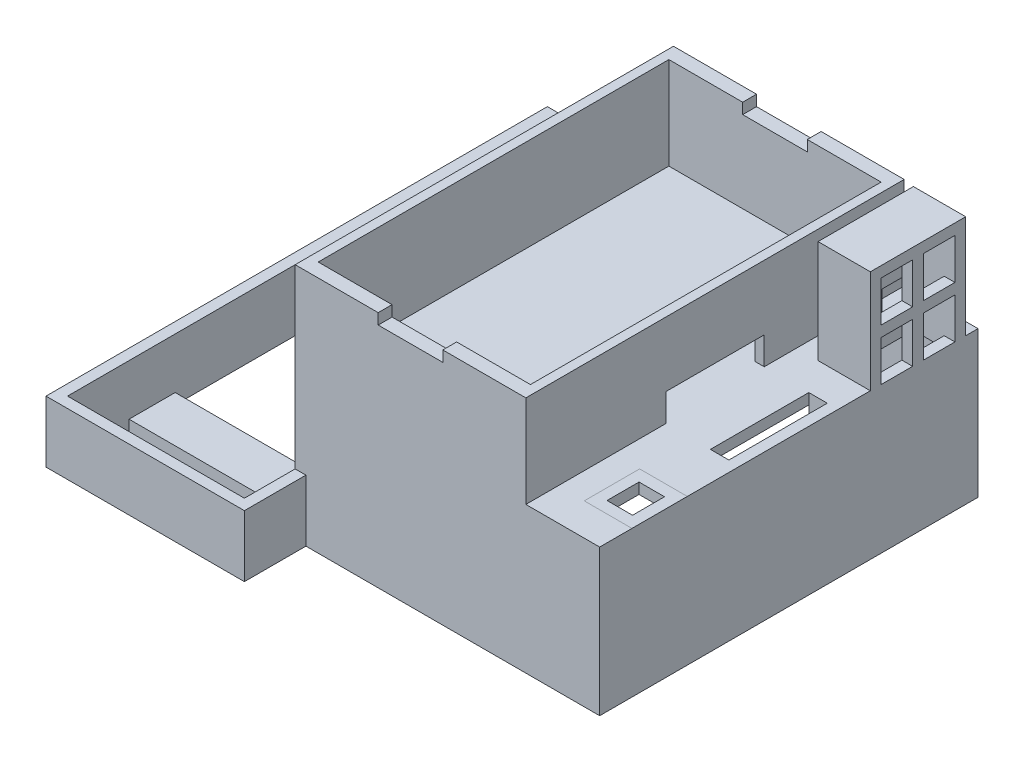
SolidWorks part; units mm, degrees
ref_plane "Front Plane" through (0, 0, 0) normal (0, 0, 1) x (1, 0, 0)
ref_plane "Top Plane" through (0, 0, 0) normal (0, 1, 0) x (1, 0, 0)
ref_plane "Right Plane" through (0, 0, 0) normal (1, 0, 0) x (0, 0, -1)
sketch "Sketch1" plane through (0, 0, 0) normal (0, 1, 0) x (1, 0, 0)
  line L1 (-138.162, -76.1412) -> (-88.662, -76.1412)
  line L2 (-138.162, -76.1412) -> (-138.162, -14.6412)
  line L3 (-138.162, -14.6412) -> (-88.662, -14.6412)
  line L4 (-88.662, -76.1412) -> (-88.662, -14.6412)
  dimension "D1" = 49.5
  dimension "D2" = 61.5
extrude "Boss-Extrude1" add sketch "Sketch1" along normal blind 23.75
sketch "Sketch2" plane through (0, 0, 0) normal (0, -1, 0) x (-1, 0, 0)
  line L0 (138.162, -76.1412) -> (88.662, -76.1412) construction
  line L1 (90.412, -74.3912) -> (136.412, -74.3912)
  line L2 (90.412, -74.3912) -> (90.412, -16.3912)
  line L3 (90.412, -16.3912) -> (136.412, -16.3912)
  line L4 (136.412, -74.3912) -> (136.412, -16.3912)
  line L5 (88.662, -76.1412) -> (88.662, -14.6412) construction
  line L6 (88.662, -14.6412) -> (138.162, -14.6412) construction
  line L7 (138.162, -14.6412) -> (138.162, -76.1412) construction
  dimension "D1" = 1.75
  dimension "D2" = 1.75
  dimension "D3" = 1.75
  dimension "D4" = 1.75
extrude "Cut-Extrude1" cut sketch "Sketch2" against normal blind 22
sketch "Sketch3" plane through (0, 22, 0) normal (0, -1, 0) x (-1, 0, 0)
  line L0 (136.412, -16.3912) -> (90.412, -16.3912) construction
  line L1 (90.412, -74.3912) -> (93.412, -74.3912)
  line L2 (90.412, -74.3912) -> (90.412, -16.3912)
  line L3 (90.412, -16.3912) -> (93.412, -16.3912)
  line L4 (93.412, -74.3912) -> (93.412, -16.3912)
  line L6 (90.412, -58.3912) -> (93.412, -58.3912)
  line L7 (90.412, -58.3912) -> (90.412, -53.3912)
  line L8 (90.412, -53.3912) -> (93.412, -53.3912)
  line L9 (93.412, -58.3912) -> (93.412, -53.3912)
  line L10 (90.412, -37.3912) -> (93.412, -37.3912)
  line L11 (90.412, -37.3912) -> (90.412, -32.3912)
  line L12 (90.412, -32.3912) -> (93.412, -32.3912)
  line L13 (93.412, -37.3912) -> (93.412, -32.3912)
  line M9 (90.412, -16.3912) -> (90.412, -74.3912)
  line M10 (90.412, -74.3912) -> (136.412, -74.3912)
  line M12 (136.412, -16.3912) -> (90.412, -16.3912)
  dimension "D1" = 3
  dimension "D2" = 5
  dimension "D3" = 5
  dimension "D4" = 16
  dimension "D5" = 16
extrude "Cut-Extrude2" cut sketch "Sketch3" against normal blind 1.75 contours L6 L2 L4 M10 | L12 L4 M9 M12 | L10 L2 L8 L4
sketch "Sketch7" plane through (0, 22, 0) normal (0, -1, 0) x (-1, 0, 0)
  line L1 (90.412, -58.3912) -> (93.412, -58.3912)
  line L2 (90.412, -58.3912) -> (90.412, -53.3912)
  line L3 (90.412, -53.3912) -> (93.412, -53.3912)
  line L4 (93.412, -58.3912) -> (93.412, -53.3912)
  line L5 (90.412, -37.3912) -> (93.412, -37.3912)
  line L6 (90.412, -37.3912) -> (90.412, -32.3912)
  line L7 (90.412, -32.3912) -> (93.412, -32.3912)
  line L8 (93.412, -37.3912) -> (93.412, -32.3912)
extrude "Boss-Extrude2" add sketch "Sketch7" along normal blind 6 contours L2 L1 L4 L3 | L6 L5 L8 L7
sketch "Sketch9" plane through (-93.412, 0, 0) normal (-1, 0, 0) x (0, 0, 1)
  line L0 (58.3912, 16) -> (58.3912, 22) construction
  line L1 (58.3912, 20.407) -> (53.3912, 20.407)
  line L2 (58.3912, 20.407) -> (58.3912, 22)
  line L3 (58.3912, 22) -> (53.3912, 22)
  line L4 (53.3912, 20.407) -> (53.3912, 22)
sketch "Sketch11" plane through (0, 23.75, 0) normal (0, 1, 0) x (1, 0, 0)
  line L0 (-138.162, -76.1412) -> (-88.662, -76.1412) construction
  line L1 (-138.162, -14.6412) -> (-100.662, -14.6412)
  line L2 (-138.162, -14.6412) -> (-138.162, -76.1412)
  line L3 (-138.162, -76.1412) -> (-100.662, -76.1412)
  line L4 (-100.662, -14.6412) -> (-100.662, -76.1412)
  dimension "D1" = 37.5
extrude "Boss-Extrude3" add sketch "Sketch11" along normal blind 15
sketch "Sketch12" plane through (0, 38.75, 0) normal (0, 1, 0) x (1, 0, 0)
  line L0 (-138.162, -14.6412) -> (-138.162, -76.1412) construction
  line L1 (-136.662, -16.8912) -> (-102.162, -16.8912)
  line L2 (-136.662, -16.8912) -> (-136.662, -73.8912)
  line L3 (-136.662, -73.8912) -> (-102.162, -73.8912)
  line L4 (-102.162, -16.8912) -> (-102.162, -73.8912)
  line L5 (-100.662, -76.1412) -> (-100.662, -14.6412) construction
  line L6 (-100.662, -14.6412) -> (-138.162, -14.6412) construction
  line L7 (-138.162, -76.1412) -> (-100.662, -76.1412) construction
  dimension "D1" = 1.5
  dimension "D2" = 1.5
  dimension "D3" = 2.25
  dimension "D4" = 2.25
extrude "Cut-Extrude3" cut sketch "Sketch12" against normal blind 15
sketch "Sketch14" plane through (0, 23.75, 0) normal (0, 1, 0) x (1, 0, 0)
  line L0 (-90.412, -58.3912) -> (-93.412, -58.3912) construction
  line L1 (-96.417, -70.8912) -> (-88.667, -70.8912)
  line L2 (-96.417, -70.8912) -> (-96.417, -61.8912)
  line L3 (-96.417, -61.8912) -> (-88.667, -61.8912)
  line L4 (-88.667, -70.8912) -> (-88.667, -61.8912)
  point P6 (-91.912, -58.3912)
  dimension "D1" = 9
  dimension "D2" = 7.75
  dimension "D3" = 3.5
  dimension "D4" = 3.245
extrude "Boss-Extrude4" add sketch "Sketch14" along normal blind 0.0001
sketch "Sketch15" plane through (0, 23.7501, 0) normal (0, 1, 0) x (1, 0, 0)
  line L0 (-96.417, -61.8912) -> (-96.417, -70.8912) construction
  line L1 (-94.617, -68.9912) -> (-90.467, -68.9912)
  line L2 (-94.617, -68.9912) -> (-94.617, -63.7912)
  line L3 (-94.617, -63.7912) -> (-90.467, -63.7912)
  line L4 (-90.467, -68.9912) -> (-90.467, -63.7912)
  line L5 (-88.667, -61.8912) -> (-96.417, -61.8912) construction
  line L6 (-88.667, -70.8912) -> (-88.667, -61.8912) construction
  line L7 (-96.417, -70.8912) -> (-88.667, -70.8912) construction
  dimension "D1" = 1.8
  dimension "D2" = 1.9
  dimension "D3" = 1.8
  dimension "D4" = 1.9
extrude "Cut-Extrude4" cut sketch "Sketch15" against normal blind 4.75
sketch "Sketch16" plane through (0, 23.75, 0) normal (0, 1, 0) x (1, 0, 0)
  line L0 (-93.412, -16.3912) -> (-90.412, -16.3912) construction
  line L1 (-97.162, -32.1412) -> (-88.662, -32.1412)
  line L2 (-97.162, -32.1412) -> (-97.162, -16.6412)
  line L3 (-97.162, -16.6412) -> (-88.662, -16.6412)
  line L4 (-88.662, -32.1412) -> (-88.662, -16.6412)
  line L5 (-93.412, -32.3912) -> (-93.412, -16.3912) construction
  point P6 (-91.912, -16.3912)
  point P9 (-93.412, -24.3912)
  dimension "D1" = 15.5
  dimension "D2" = 8.5
  dimension "D3" = 3.25
  dimension "D4" = 7.75
extrude "Boss-Extrude5" add sketch "Sketch16" along normal blind 16.75
sketch "Sketch17" plane through (-88.662, 0, 0) normal (1, 0, 0) x (0, 0, -1)
  line L0 (-32.1412, 40.5) -> (-16.6412, 40.5) construction
  line L1 (-30.3912, 38.75) -> (-25.2662, 38.75)
  line L2 (-30.3912, 38.75) -> (-30.3912, 23.75)
  line L3 (-30.3912, 23.75) -> (-25.2662, 23.75)
  line L4 (-25.2662, 38.75) -> (-25.2662, 23.75)
  line L5 (-23.5162, 38.75) -> (-18.3912, 38.75)
  line L6 (-23.5162, 38.75) -> (-23.5162, 23.75)
  line L7 (-23.5162, 23.75) -> (-18.3912, 23.75)
  line L8 (-18.3912, 38.75) -> (-18.3912, 23.75)
  line L9 (-32.1412, 40.5) -> (-32.1412, 23.75) construction
  line L10 (-16.6412, 40.5) -> (-16.6412, 23.75) construction
  line L11 (-16.6412, 23.75) -> (-14.6412, 23.75) construction
  line L12 (-76.1412, 23.75) -> (-32.1412, 23.75) construction
  line L14 (-32.1412, 32.125) -> (-16.6412, 32.125)
  line L15 (-32.1412, 32.125) -> (-32.1412, 30.375)
  line L16 (-32.1412, 30.375) -> (-16.6412, 30.375)
  line L17 (-16.6412, 32.125) -> (-16.6412, 30.375)
  dimension "D1" = 1.75
  dimension "D2" = 1.75
  dimension "D3" = 1.75
  dimension "D4" = 1.75
  dimension "D5" = 0
  dimension "D6" = 0
  dimension "D7" = 5.125
  dimension "D8" = 5.125
  dimension "D9" = 1.75
  dimension "D10" = 6.625
extrude "Cut-Extrude5" cut sketch "Sketch17" against normal blind 8.5 contours L2 L14 L4 L1 | L16 L2 L3 L4 | L6 L14 L8 L5 | L16 L6 L7 L8
sketch "Sketch18" plane through (0, 23.75, 0) normal (0, 1, 0) x (1, 0, 0)
  line L0 (-93.412, -18.3912) -> (-90.412, -18.3912) construction
  line L1 (-95.412, -30.3912) -> (-90.412, -30.3912)
  line L2 (-95.412, -30.3912) -> (-95.412, -18.3912)
  line L3 (-95.412, -18.3912) -> (-90.412, -18.3912)
  line L4 (-90.412, -30.3912) -> (-90.412, -18.3912)
  line L5 (-88.662, -30.3912) -> (-88.662, -25.2662) construction
  line L6 (-93.412, -30.3912) -> (-90.412, -30.3912) construction
  dimension "D1" = 0
  dimension "D2" = 1.75
  dimension "D3" = 1.75
  dimension "D4" = 0
extrude "Cut-Extrude6" cut sketch "Sketch18" against normal blind 1.75 and the other way blind 15
sketch "Sketch20" plane through (-100.662, 0, 0) normal (1, 0, 0) x (0, 0, -1)
  line L0 (-76.1412, 23.75) -> (-14.6412, 23.75) construction
  line L1 (-53.3912, 28.25) -> (-37.3912, 28.25)
  line L2 (-53.3912, 28.25) -> (-53.3912, 23.75)
  line L3 (-53.3912, 23.75) -> (-37.3912, 23.75)
  line L4 (-37.3912, 28.25) -> (-37.3912, 23.75)
  dimension "D1" = 4.5
  dimension "D2" = 0
  dimension "D3" = 0
extrude "Cut-Extrude7" cut sketch "Sketch20" against normal blind 1.75
sketch "Sketch21" plane through (0, 0, 0) normal (0, -1, 0) x (-1, 0, 0)
  line L0 (138.162, -14.6412) -> (138.162, -76.1412) construction
  line L1 (136.412, -86.1412) -> (168.662, -86.1412)
  line L2 (136.412, -86.1412) -> (136.412, -4.6412)
  line L3 (136.412, -4.6412) -> (168.662, -4.6412)
  line L4 (168.662, -86.1412) -> (168.662, -4.6412)
  line L5 (138.162, -76.1412) -> (88.662, -76.1412) construction
  line L6 (88.662, -14.6412) -> (138.162, -14.6412) construction
  dimension "D1" = 30.5
  dimension "D2" = 1.75
  dimension "D3" = 10
  dimension "D4" = 10
extrude "Boss-Extrude7" add sketch "Sketch21" against normal blind 10
sketch "Sketch23" plane through (0, 10, 0) normal (0, 1, 0) x (1, 0, 0)
  line L0 (-136.412, -86.1412) -> (-168.662, -86.1412) construction
  line L1 (-138.162, -84.3912) -> (-166.912, -84.3912)
  line L2 (-138.162, -84.3912) -> (-138.162, -6.3912)
  line L3 (-138.162, -6.3912) -> (-166.912, -6.3912)
  line L4 (-166.912, -84.3912) -> (-166.912, -6.3912)
  line L5 (-168.662, -86.1412) -> (-168.662, -4.6412) construction
  line L6 (-168.662, -4.6412) -> (-136.412, -4.6412) construction
  line L7 (-138.162, -14.6412) -> (-138.162, -76.1412) construction
  dimension "D1" = 1.75
  dimension "D2" = 1.75
  dimension "D3" = 1.75
  dimension "D4" = 0
extrude "Cut-Extrude8" cut sketch "Sketch23" against normal blind 10
sketch "Sketch24" plane through (0, 23.75, 0) normal (0, -1, 0) x (-1, 0, 0)
  line L1 (93.383, -63.5335) -> (90.412, -63.5335)
  line L2 (93.383, -63.5335) -> (93.383, -58.3912)
  line L3 (93.383, -58.3912) -> (90.412, -58.3912)
  line L4 (90.412, -63.5335) -> (90.412, -58.3912)
sketch "Sketch25" plane through (0, 22, 0) normal (0, -1, 0) x (-1, 0, 0)
  line L0 (90.412, -63.5335) -> (90.412, -58.3912) construction
  line L1 (93.412, -63.7912) -> (90.412, -63.7912)
  line L2 (93.412, -63.7912) -> (93.412, -58.3912)
  line L3 (93.412, -58.3912) -> (90.412, -58.3912)
  line L4 (90.412, -63.7912) -> (90.412, -58.3912)
  line L5 (93.383, -58.3912) -> (90.412, -58.3912) construction
  line L6 (93.412, -74.3912) -> (136.412, -74.3912) construction
  line L7 (93.412, -68.9912) -> (90.412, -68.9912)
  line L8 (93.412, -68.9912) -> (93.412, -74.3912)
  line L9 (93.412, -74.3912) -> (90.412, -74.3912)
  line L10 (90.412, -68.9912) -> (90.412, -74.3912)
  line L11 (90.412, -70.8912) -> (90.412, -61.8912) construction
  dimension "D1" = 0
  dimension "D2" = 0
  dimension "D3" = 0
  dimension "D4" = 0
extrude "Boss-Extrude8" add sketch "Sketch25" against normal blind 1.75
sketch "Sketch26" plane through (0, 23.75, 0) normal (0, 1, 0) x (1, 0, 0)
  line L1 (-93.412, -32.3912) -> (-90.412, -32.3912)
  line L2 (-93.412, -32.3912) -> (-93.412, -30.3912)
  line L3 (-93.412, -30.3912) -> (-90.412, -30.3912)
  line L4 (-90.412, -32.3912) -> (-90.412, -30.3912)
sketch "Sketch28" plane through (0, 23.75, 0) normal (0, 1, 0) x (1, 0, 0)
  line L0 (-90.412, -23.5162) -> (-90.412, -18.3912) construction
  line L1 (-93.412, -16.3912) -> (-90.412, -16.3912)
  line L2 (-93.412, -16.3912) -> (-93.412, -18.3912)
  line L3 (-93.412, -18.3912) -> (-90.412, -18.3912)
  line L4 (-90.412, -16.3912) -> (-90.412, -18.3912)
  line L6 (-90.412, -32.3912) -> (-93.412, -32.3912)
  line L7 (-90.412, -32.3912) -> (-90.412, -30.3912)
  line L8 (-90.412, -30.3912) -> (-93.412, -30.3912)
  line L9 (-93.412, -32.3912) -> (-93.412, -30.3912)
extrude "Boss-Extrude9" add sketch "Sketch28" against normal blind 1.75
sketch "Sketch30" plane through (-93.412, 0, 0) normal (-1, 0, 0) x (0, 0, 1)
  line L0 (58.3912, 16) -> (58.3912, 22) construction
  line L1 (58.3912, 16) -> (53.3912, 16)
  line L2 (58.3912, 16) -> (58.3912, 17.5)
  line L3 (58.3912, 17.5) -> (53.3912, 17.5)
  line L4 (53.3912, 16) -> (53.3912, 17.5)
  line L5 (53.3912, 16) -> (53.3912, 22) construction
  line L6 (37.3912, 16) -> (37.3912, 22) construction
  line L7 (37.3912, 16) -> (32.3912, 16)
  line L8 (37.3912, 16) -> (37.3912, 17.5)
  line L9 (37.3912, 17.5) -> (32.3912, 17.5)
  line L10 (32.3912, 16) -> (32.3912, 17.5)
  line L11 (32.3912, 16) -> (32.3912, 22) construction
  dimension "D1" = 1.5
  dimension "D2" = 1.5
extrude "Boss-Extrude11" add sketch "Sketch30" along normal blind 1
sketch "Sketch32" plane through (0, 38.75, 0) normal (0, 1, 0) x (1, 0, 0)
  line L0 (-136.662, -73.8912) -> (-102.162, -73.8912) construction
  line L1 (-124.662, -73.8912) -> (-114.162, -73.8912)
  line L2 (-124.662, -73.8912) -> (-124.662, -76.1412)
  line L3 (-124.662, -76.1412) -> (-114.162, -76.1412)
  line L4 (-114.162, -73.8912) -> (-114.162, -76.1412)
  line L5 (-138.162, -76.1412) -> (-100.662, -76.1412) construction
  line L6 (-100.662, -14.6412) -> (-138.162, -14.6412) construction
  line L7 (-124.662, -14.6412) -> (-114.162, -14.6412)
  line L8 (-124.662, -14.6412) -> (-124.662, -16.8912)
  line L9 (-124.662, -16.8912) -> (-114.162, -16.8912)
  line L10 (-114.162, -14.6412) -> (-114.162, -16.8912)
  line L11 (-102.162, -16.8912) -> (-136.662, -16.8912) construction
  line L12 (-136.662, -16.8912) -> (-136.662, -73.8912) construction
  line L13 (-102.162, -73.8912) -> (-102.162, -16.8912) construction
  dimension "D1" = 12
  dimension "D2" = 12
  dimension "D3" = 12
  dimension "D4" = 12
extrude "Cut-Extrude9" cut sketch "Sketch32" against normal blind 1.75
sketch "Sketch33" plane through (-90.412, 0, 0) normal (-1, 0, 0) x (0, 0, 1)
  line L0 (16.3912, 0) -> (74.3912, 0) construction
  line L1 (27.3912, 0) -> (38.3912, 0)
  line L2 (27.3912, 0) -> (27.3912, 11)
  line L3 (27.3912, 11) -> (38.3912, 11)
  line L4 (38.3912, 0) -> (38.3912, 11)
  line L5 (16.3912, 22) -> (16.3912, 0) construction
  dimension "D1" = 11
  dimension "D2" = 11
  dimension "D3" = 0
  dimension "D4" = 11
extrude "Cut-Extrude10" cut sketch "Sketch33" against normal blind 1
sketch "Sketch34" plane through (-90.412, 0, 0) normal (-1, 0, 0) x (0, 0, 1)
  line L0 (16.3912, 0) -> (27.3912, 0) construction
  line L1 (27.3912, 0) -> (26.3912, 0)
  line L2 (27.3912, 0) -> (27.3912, 12)
  line L3 (27.3912, 12) -> (26.3912, 12)
  line L4 (26.3912, 0) -> (26.3912, 12)
  line L5 (27.3912, 11) -> (27.3912, 0) construction
  line L6 (38.3912, 0) -> (39.3912, 0)
  line L7 (38.3912, 0) -> (38.3912, 12)
  line L8 (38.3912, 12) -> (39.3912, 12)
  line L9 (39.3912, 0) -> (39.3912, 12)
  line L10 (38.3912, 12) -> (27.3912, 12)
  line L11 (38.3912, 12) -> (38.3912, 11)
  line L12 (38.3912, 11) -> (27.3912, 11)
  line L13 (27.3912, 12) -> (27.3912, 11)
  line M8 (16.3912, 0) -> (27.3912, 0)
  line M9 (27.3912, 0) -> (27.3912, 11)
  line M10 (27.3912, 11) -> (38.3912, 11)
  line M11 (38.3912, 11) -> (38.3912, 0)
  line M12 (38.3912, 0) -> (74.3912, 0)
  dimension "D1" = 1
  dimension "D2" = 0
  dimension "D3" = 1
  dimension "D4" = 1
  dimension "D5" = 0
extrude "Boss-Extrude12" add sketch "Sketch34" along normal blind 2 contours L7 L10 L2 M10 | L9 L8 L7 M12 M11 | L4 L2 L3 M8 M9
sketch "Sketch35" plane through (0, 0, 14.6412) normal (0, 0, -1) x (-1, 0, 0)
  line L0 (88.662, 0) -> (136.412, 0) construction
  line L1 (136.412, 0) -> (136.412, 10) construction
  line L2 (113.912, 0) -> (132.912, 0)
  line L3 (113.912, 0) -> (113.912, 10)
  line L4 (113.912, 10) -> (132.912, 10)
  line L5 (132.912, 0) -> (132.912, 10)
  point P0 (132.0355, 5.5243)
  point P7 (123.412, 10)
  dimension "D1" = 10
  dimension "D2" = 19
  dimension "D3" = 0
  dimension "D4" = 13
extrude "Cut-Extrude11" cut sketch "Sketch35" against normal blind 1.75
sketch "Sketch36" plane through (0, 0, 0) normal (0, -1, 0) x (-1, 0, 0)
  line L0 (136.412, -74.3912) -> (136.412, -16.3912) construction
  line L1 (136.412, -56.1412) -> (138.162, -56.1412)
  line L2 (136.412, -56.1412) -> (136.412, -34.6412)
  line L3 (136.412, -34.6412) -> (138.162, -34.6412)
  line L4 (138.162, -56.1412) -> (138.162, -34.6412)
  line L5 (138.162, -84.3912) -> (138.162, -6.3912) construction
  line L6 (136.412, -86.1412) -> (168.662, -86.1412) construction
  line L7 (168.662, -4.6412) -> (136.412, -4.6412) construction
  dimension "D1" = 30
  dimension "D2" = 30
extrude "Cut-Extrude12" cut sketch "Sketch36" against normal blind 5.75
sketch "Sketch37" plane through (0, 0, 0) normal (0, -1, 0) x (-1, 0, 0)
  line L1 (90.412, -74.3912) -> (97.912, -74.3912)
  line L2 (90.412, -74.3912) -> (90.412, -66.8912)
  line L3 (90.412, -66.8912) -> (97.912, -66.8912)
  line L4 (97.912, -74.3912) -> (97.912, -66.8912)
  line L5 (90.412, -16.3912) -> (97.912, -16.3912)
  line L6 (90.412, -16.3912) -> (90.412, -23.8912)
  line L7 (90.412, -23.8912) -> (97.912, -23.8912)
  line L8 (97.912, -16.3912) -> (97.912, -23.8912)
  line L9 (138.162, -84.3912) -> (138.162, -56.1412) construction
  line L10 (138.162, -74.3912) -> (166.912, -74.3912)
  line L11 (138.162, -74.3912) -> (138.162, -66.8912)
  line L12 (138.162, -66.8912) -> (166.912, -66.8912)
  line L13 (166.912, -74.3912) -> (166.912, -66.8912)
  line L14 (166.912, -6.3912) -> (166.912, -84.3912) construction
  line L15 (138.162, -34.6412) -> (138.162, -6.3912) construction
  line L16 (138.162, -23.8912) -> (166.912, -23.8912)
  line L17 (138.162, -23.8912) -> (138.162, -16.3912)
  line L18 (138.162, -16.3912) -> (166.912, -16.3912)
  line L19 (166.912, -23.8912) -> (166.912, -16.3912)
  line L20 (138.162, -6.3912) -> (166.912, -6.3912) construction
  line L21 (166.912, -84.3912) -> (138.162, -84.3912) construction
  dimension "D1" = 7.5
  dimension "D2" = 7.5
  dimension "D3" = 7.5
  dimension "D4" = 7.5
  dimension "D5" = 7.5
  dimension "D6" = 7.5
  dimension "D7" = 10
  dimension "D8" = 10
extrude "Boss-Extrude13" add sketch "Sketch37" against normal blind 1.75
